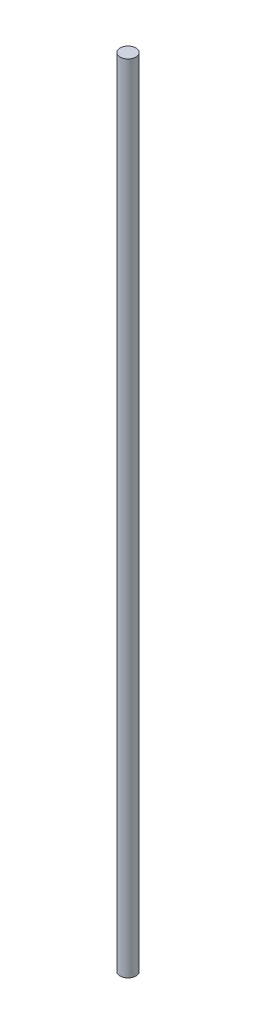
SolidWorks part; units mm, degrees
ref_plane "Front Plane" through (0, 0, 0) normal (0, 0, 1) x (1, 0, 0)
ref_plane "Top Plane" through (0, 0, 0) normal (0, 1, 0) x (1, 0, 0)
ref_plane "Right Plane" through (0, 0, 0) normal (1, 0, 0) x (0, 0, -1)
sketch "Sketch1" plane through (0, 0, 0) normal (0, 1, 0) x (1, 0, 0)
  circle A1 centre (0, 0) radius 4
  dimension "D1" = 8
extrude "Boss-Extrude1" add sketch "Sketch1" along normal blind 400 contours A1
